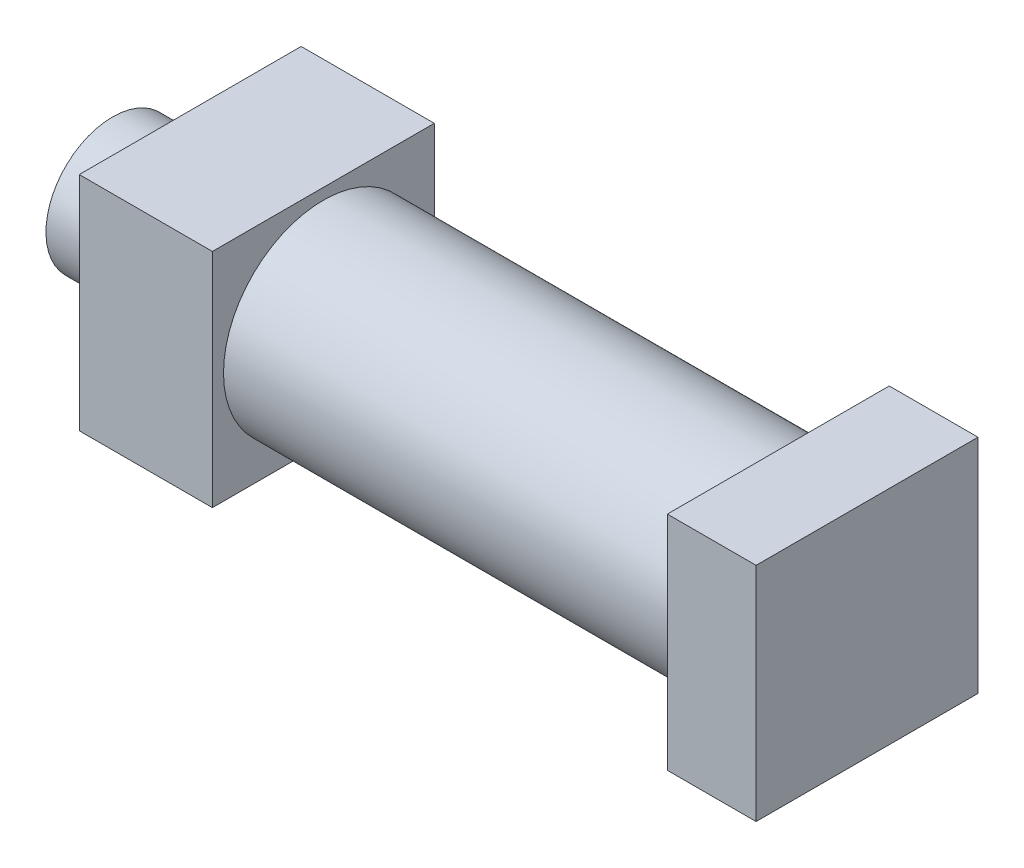
SolidWorks part; units mm, degrees
material "PW50:5:C1:0:1:2:Re:10:"
ref_plane "front" through (0, 0, 0) normal (0, 0, 1) x (1, 0, 0)
ref_plane "top" through (0, 0, 0) normal (0, 1, 0) x (1, 0, 0)
ref_plane "side" through (0, 0, 0) normal (1, 0, 0) x (0, 0, -1)
sketch "Sketch1" plane through (0, 0, 0) normal (1, 0, 0) x (0, 0, -1)
  line L0 (-31.75, 31.75) -> (31.75, 31.75)
  line L1 (-31.75, 31.75) -> (-31.75, -31.75)
  line L2 (31.75, -31.75) -> (-31.75, -31.75)
  line L3 (31.75, -31.75) -> (31.75, 31.75)
  line L4 (0, 31.75) -> (0, 0) construction
  line L5 (31.75, 0) -> (0, 0) construction
  dimension "E" = 63.5
extrude "Base-Extrude" add sketch "Sketch1" against normal blind 25.4
sketch "STROKE" plane through (0, 0, 0) normal (0, 0, 1) x (1, 0, 0)
  line L0 (0, 0) -> (-101.6, 0) construction
  line L1 (-101.6, 0) -> (-193.675, 0) construction
  dimension "STROKE" = 101.6
  dimension "LB" = 92.075
ref_plane "LB + STROKE" through (-193.675, 0, 0) normal (-1, 0, 0) x (0, 0, 1)
sketch "Sketch2" plane through (0, 0, 0) normal (-1, 0, 0) x (0, 0, 1)
  line L0 (0, 0) -> (28.575, 0) construction
  circle A0 centre (0, 0) radius 28.575
  circle A1 centre (0, 0) radius 25.4
  point P5 (25.4, 0)
  dimension "D1" = 3.175
  dimension "BORE" = 50.8
extrude "BORE" add sketch "Sketch2" along normal up to surface (193.675 mm away) up to plane "LB + STROKE"
sketch "Sketch3" plane through (-193.675, 0, 0) normal (-1, 0, 0) x (0, 0, 1)
  line L2 (31.75, 31.75) -> (-31.75, 31.75)
  line L3 (31.75, 31.75) -> (-31.75, 31.75)
  line L4 (31.75, -31.75) -> (31.75, 31.75)
  line L7 (-31.75, 31.75) -> (-31.75, -31.75)
  line L8 (31.75, -31.75) -> (31.75, 31.75)
  line L9 (-31.75, 31.75) -> (-31.75, -31.75)
  line L10 (-31.75, -31.75) -> (31.75, -31.75)
  line L11 (-31.75, -31.75) -> (31.75, -31.75)
  dimension "D1" = 0
extrude "Boss-Extrude2" add sketch "Sketch3" against normal blind 38.1
sketch "Sketch4" plane through (-193.675, 0, 0) normal (1, 0, 0) x (0, 0, -1)
  circle A0 centre (0, 0) radius 19.05
  dimension "B" = 38.1
extrude "Boss-Extrude3" add sketch "Sketch4" against normal blind 22.225
sketch "Sketch5" plane through (-215.9, 0, 0) normal (-1, 0, 0) x (0, 0, 1)
  circle A0 centre (0, 0) radius 12.7
  dimension "MM_ROD_DIA" = 25.4
extrude "Cut-Extrude1" cut sketch "Sketch5" against normal up to surface (190.5 mm away)
sketch "Sketch6" plane through (148.5418, -31.75, 0.8139) normal (0, -1, 0) x (1, 0, 0)
  line L0 (-161.2418, 30.9361) -> (-161.2418, -11.9264) construction
  line L1 (-323.1668, 30.9361) -> (-323.1668, -32.5639) construction
  line L2 (-173.9418, -0.8139) -> (-138.5475, -0.8139) construction
  line L3 (-304.1168, 30.9361) -> (-342.2168, 30.9361) construction
  line L4 (-173.9418, -32.5639) -> (-173.9418, 30.9361) construction
  line L5 (-173.9418, 30.9361) -> (-148.5418, 30.9361) construction
  line L6 (-304.1168, -32.5639) -> (-342.2168, -32.5639) construction
  line L7 (-161.2418, -11.9264) -> (-323.1668, -11.9264) construction
  circle A0 centre (-161.2418, 10.2986) radius 3.9687
  circle A2 centre (-161.2418, -11.9264) radius 3.9687
  circle A3 centre (-323.1668, -11.9264) radius 3.9687
  circle A4 centre (-323.1668, 10.2986) radius 3.9687
  dimension "D1" = 22.225
  dimension "RD" = 7.9375
extrude "TAPPED BASE HOLES - MS4" cut sketch "Sketch6" against normal blind 19.05
sketch "Sketch10" plane through (0, 0, 0) normal (0, 0, 1) x (1, 0, 0)
  line L0 (-174.625, 31.75) -> (-174.625, -31.75) construction
  line L1 (-155.575, 31.75) -> (-193.675, 31.75) construction
  line L2 (-155.575, -31.75) -> (-193.675, -31.75) construction
  circle A0 centre (-174.625, 0) radius 12.7
  dimension "TD" = 25.4
extrude "HEAD TRUNION - MT1" [suppressed] add sketch "Sketch10" along normal mid plane 114.3
sketch "Sketch11" plane through (0, 0, 0) normal (0, 0, 1) x (1, 0, 0)
  line L0 (0, 0) -> (29.8231, 0) construction
  line L1 (-155.575, 0) -> (-215.9, 0) construction
  line L2 (31.75, -9.525) -> (31.75, 9.525)
  line L3 (31.75, 9.525) -> (0, 21.0811)
  line L4 (0, 31.75) -> (0, -31.75) construction
  line L5 (0, 21.0811) -> (0, -21.0811)
  line L6 (31.75, -9.525) -> (0, -21.0811)
  circle A0 centre (19.05, 0) radius 15.875 construction
  circle A1 centre (19.05, 0) radius 6.3627
  point P10 (0, 0)
  point P12 (31.75, 0)
  dimension "MR" = 15.875
  dimension "CD" = 12.7254
  dimension "D2" = 70
  dimension "L" = 19.05
  dimension "M" = 12.7
extrude "CAP EYE - MP3" [suppressed] add sketch "Sketch11" along normal mid plane 19.05
